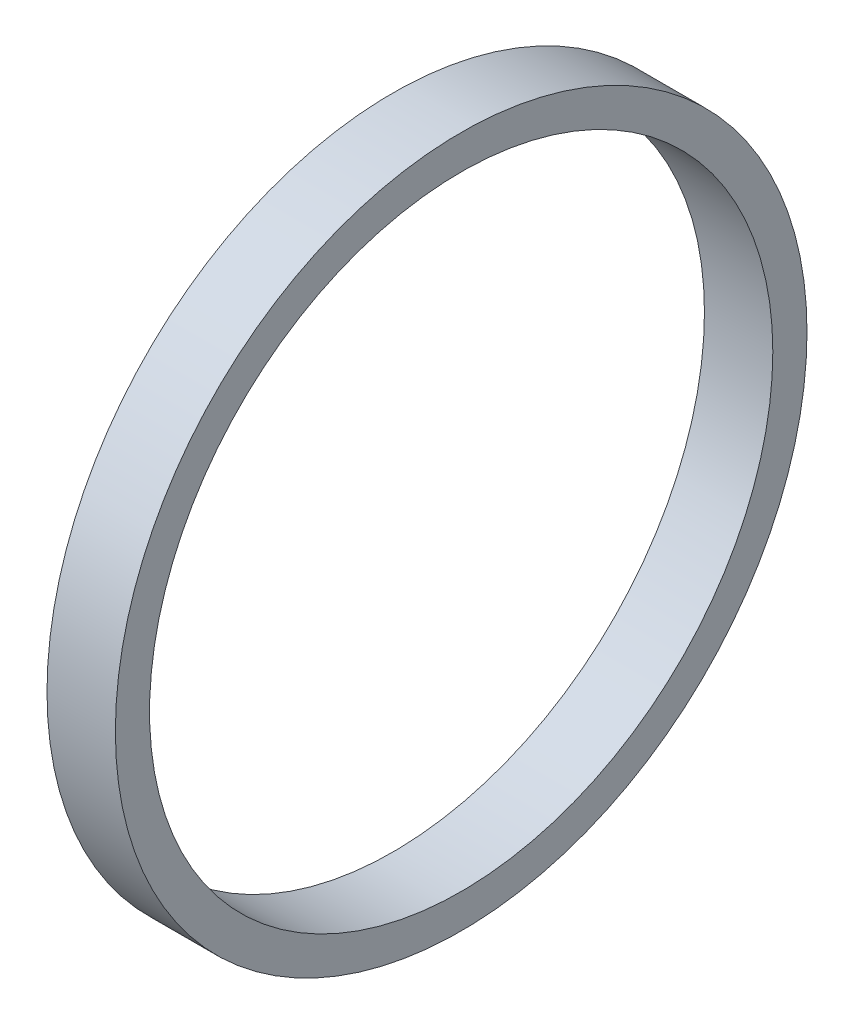
SolidWorks part; units mm, degrees
ref_plane "Front Plane" through (0, 0, 0) normal (0, 0, 1) x (1, 0, 0)
ref_plane "Top Plane" through (0, 0, 0) normal (0, 1, 0) x (1, 0, 0)
ref_plane "Right Plane" through (0, 0, 0) normal (1, 0, 0) x (0, 0, -1)
sketch "Sketch2" plane through (-607.2833, -0.3781, -0.4009) normal (1, 0, 0) x (0, 0.7275, -0.6861)
  line L0 (27.35, 0.5511) -> (30.35, 0.5511) construction
  line L1 (27.25, 0.5511) -> (27.35, 0.5511) construction
  circle A0 centre (0, 0.5511) radius 27.25 construction
  circle A1 centre (0, 0.5511) radius 27.25 construction
  circle A2 centre (0, 0.5511) radius 30.35
  circle A3 centre (0, 0.5511) radius 27.35
  dimension "D1" = 3
  dimension "D2" = 0.1
extrude "Boss-Extrude1" add sketch "Sketch2" against normal blind 6
